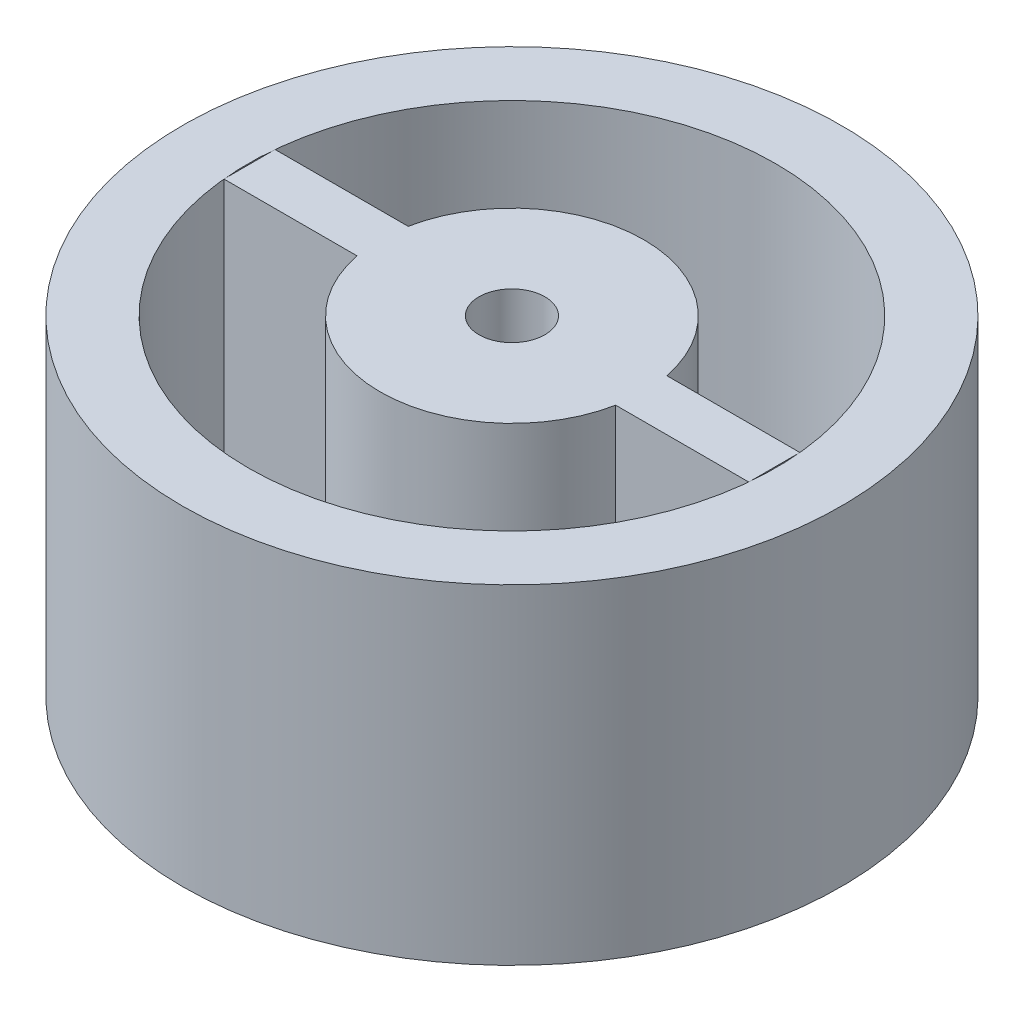
SolidWorks part; units mm, degrees
material "Rubber"
ref_plane "Front Plane" through (0, 0, 0) normal (0, 0, 1) x (1, 0, 0)
ref_plane "Top Plane" through (0, 0, 0) normal (0, 1, 0) x (1, 0, 0)
ref_plane "Right Plane" through (0, 0, 0) normal (1, 0, 0) x (0, 0, -1)
sketch "Sketch2" plane through (0, 0, 0) normal (0, 1, 0) x (1, 0, 0)
  circle A0 centre (0, 0) radius 5
  circle A1 centre (0, 0) radius 0.5
  dimension "D1" = 10
  dimension "D2" = 1
extrude "Boss-Extrude1" add sketch "Sketch2" along normal blind 5
sketch "Sketch4" plane through (0, 0, 0) normal (0, -1, 0) x (1, 0, 0)
  circle A0 centre (0, 0) radius 4
  circle A1 centre (0, 0) radius 2
  dimension "D1" = 8
  dimension "D2" = 4
extrude "Cut-Extrude1" cut sketch "Sketch4" against normal through all both and the other way through all
sketch "Sketch5" plane through (0, 0, 0) normal (0, -1, 0) x (1, 0, 0)
  line L1 (-3.9812, -0.3878) -> (3.9812, -0.3878)
  line L2 (-3.9812, -0.3878) -> (-3.9812, 0.3878)
  line L3 (-3.9812, 0.3878) -> (3.9812, 0.3878)
  line L4 (3.9812, -0.3878) -> (3.9812, 0.3878)
  line L5 (-3.9812, -0.3878) -> (3.9812, 0.3878) construction
  line L6 (-3.9812, 0.3878) -> (3.9812, -0.3878) construction
  circle A0 centre (0, 0) radius 4 construction
  point P0 (0, 0)
extrude "Boss-Extrude2" add sketch "Sketch5" against normal blind 5
sketch "Sketch6" plane through (0, 0, 0) normal (0, -1, 0) x (1, 0, 0)
  circle A0 centre (0, 0) radius 0.5
extrude "Cut-Extrude2" cut sketch "Sketch6" against normal through all both and the other way through all
scale "Scale1" bodies to scale 105 102 scale about centroid uniform scaling yes scale factor 6
